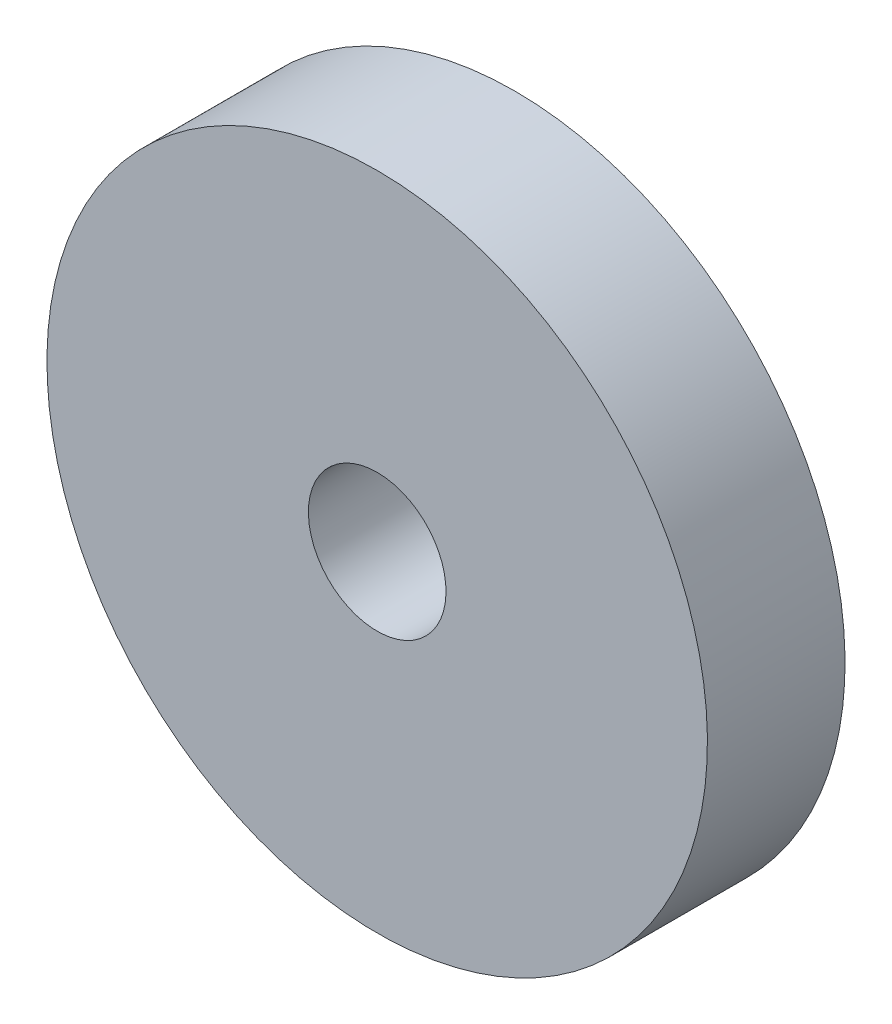
SolidWorks part; units mm, degrees
ref_plane "前视基准面" through (0, 0, 0) normal (0, 0, 1) x (1, 0, 0)
ref_plane "上视基准面" through (0, 0, 0) normal (0, 1, 0) x (1, 0, 0)
ref_plane "右视基准面" through (0, 0, 0) normal (1, 0, 0) x (0, 0, -1)
ref_plane "基准面4" through (0, 0, 0) normal (0, -1, 0) x (1, 0, 0)
sketch "草图1" plane through (0, 0, 0) normal (0, -1, 0) x (1, 0, 0)
  line L0 (0.25, 7.5) -> (5, 7.5)
  line L1 (5, 7.5) -> (5, 10)
  line L2 (5, 10) -> (0.25, 10)
  line L3 (0.25, 10) -> (0.25, 7.5)
  line L4 (-1, 10) -> (-1, 0) construction
  dimension "D1" = 4.75
  dimension "D2" = 2.5
  dimension "D3" = 6
revolve "旋转1" add sketch "草图1" angle 360 about L4
scale "缩放比例1" scale about centroid uniform scaling yes scale factor 2
